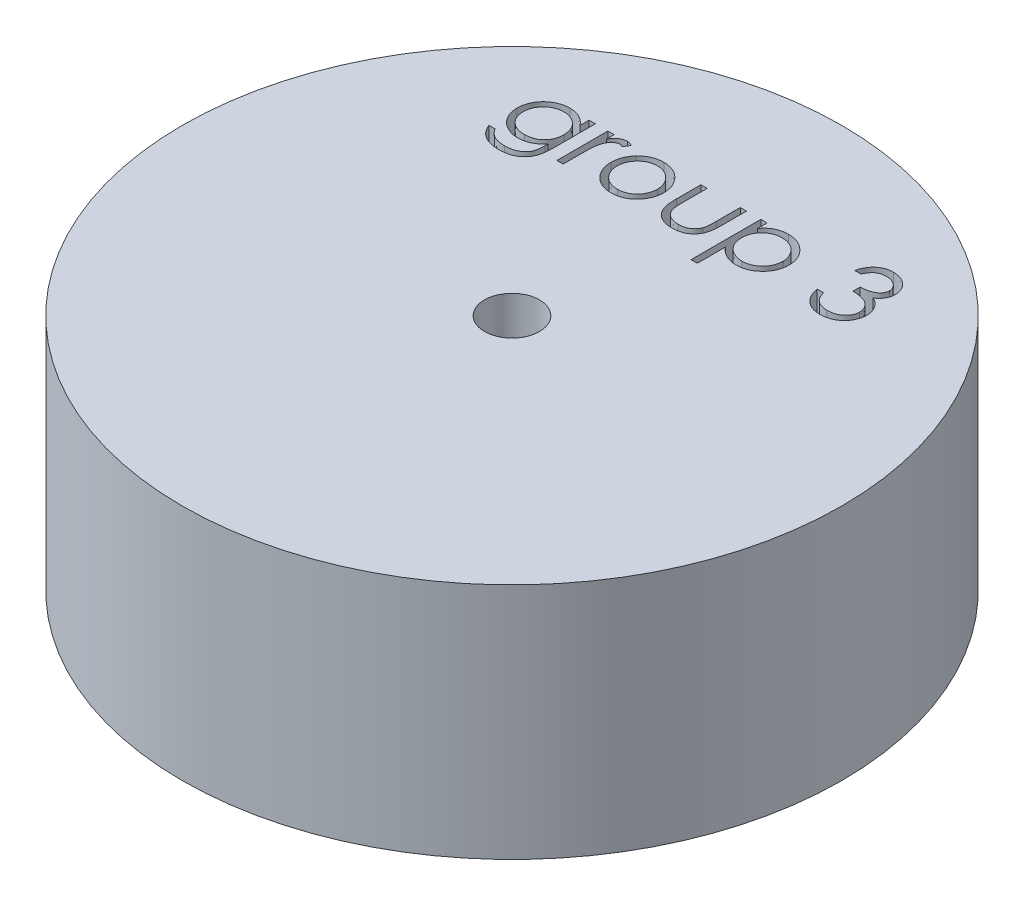
SolidWorks part; units mm, degrees
ref_plane "Front Plane" through (0, 0, 0) normal (0, 0, 1) x (1, 0, 0)
ref_plane "Top Plane" through (0, 0, 0) normal (0, 1, 0) x (1, 0, 0)
ref_plane "Right Plane" through (0, 0, 0) normal (1, 0, 0) x (0, 0, -1)
sketch "Sketch1" plane through (0, 0, 0) normal (0, 1, 0) x (1, 0, 0)
  circle A0 centre (0, 0) radius 15
  dimension "D1" = 30
extrude "Boss-Extrude2" add sketch "Sketch1" along normal blind 10.82 contours A0
sketch "Sketch2" plane through (0, 10.82, 0) normal (0, 1, 0) x (1, 0, 0)
  circle A0 centre (0, 0) radius 1.25
  dimension "D1" = 2.5
extrude "Cut-Extrude1" cut sketch "Sketch2" against normal blind 7.65
sketch "Sketch3" plane through (0, 10.82, 0) normal (0, 1, 0) x (1, 0, 0)
  line L0 (-8.3109, 7.1361) -> (9.8338, 7.1361) construction
  text T0 "group 3\r\n"
extrude "Cut-Extrude2" cut sketch "Sketch3" against normal blind 2
